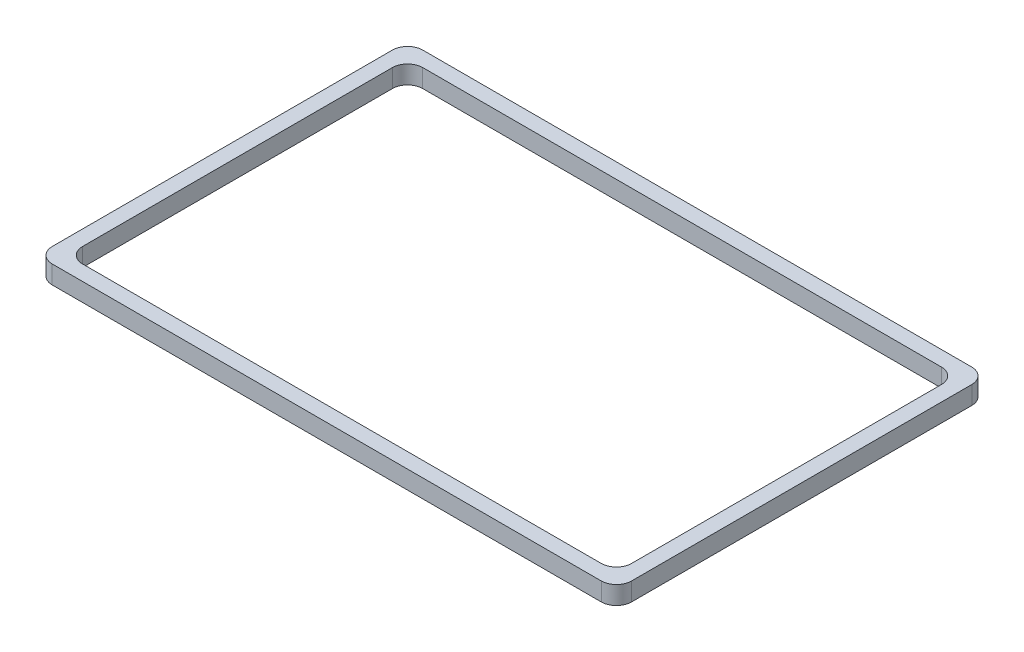
SolidWorks part; units mm, degrees
ref_plane "前视基准面" through (0, 0, 0) normal (0, 0, 1) x (1, 0, 0)
ref_plane "上视基准面" through (0, 0, 0) normal (0, 1, 0) x (1, 0, 0)
ref_plane "右视基准面" through (0, 0, 0) normal (1, 0, 0) x (0, 0, -1)
sketch "草图1" plane through (0, 0, 0) normal (0, 1, 0) x (1, 0, 0)
  line L5 (-171, 112.15) -> (171, 112.15)
  line L6 (-181, 102.15) -> (-181, -102.15)
  line L7 (-171, -112.15) -> (171, -112.15)
  line L8 (181, 102.15) -> (181, -102.15)
  line L9 (-181, 122.15) -> (181, 122.15)
  line L10 (-191, 112.15) -> (-191, -112.15)
  line L11 (-181, -122.15) -> (181, -122.15)
  line L12 (191, 112.15) -> (191, -112.15)
  arc A0 (-171, 112.15) -> (-181, 102.15) centre (-171, 102.15) ccw
  arc A1 (171, 112.15) -> (181, 102.15) centre (171, 102.15) cw
  arc A2 (171, -112.15) -> (181, -102.15) centre (171, -102.15) ccw
  arc A3 (-181, -102.15) -> (-171, -112.15) centre (-171, -102.15) ccw
  arc A4 (-181, 122.15) -> (-191, 112.15) centre (-181, 112.15) ccw
  arc A5 (181, 122.15) -> (191, 112.15) centre (181, 112.15) cw
  arc A6 (181, -122.15) -> (191, -112.15) centre (181, -112.15) ccw
  arc A7 (-191, -112.15) -> (-181, -122.15) centre (-181, -112.15) ccw
  point P24 (-191, 0)
  point P26 (0, -112.15)
  point P27 (-181, 0)
  dimension "D1" = 10
  dimension "D2" = 10
  dimension "D3" = 10
  dimension "D4" = 10
  dimension "D5" = 10
  dimension "D6" = 10
  dimension "D7" = 342
  dimension "D8" = 204.3
extrude "凸台-拉伸1" add sketch "草图1" along normal blind 12
